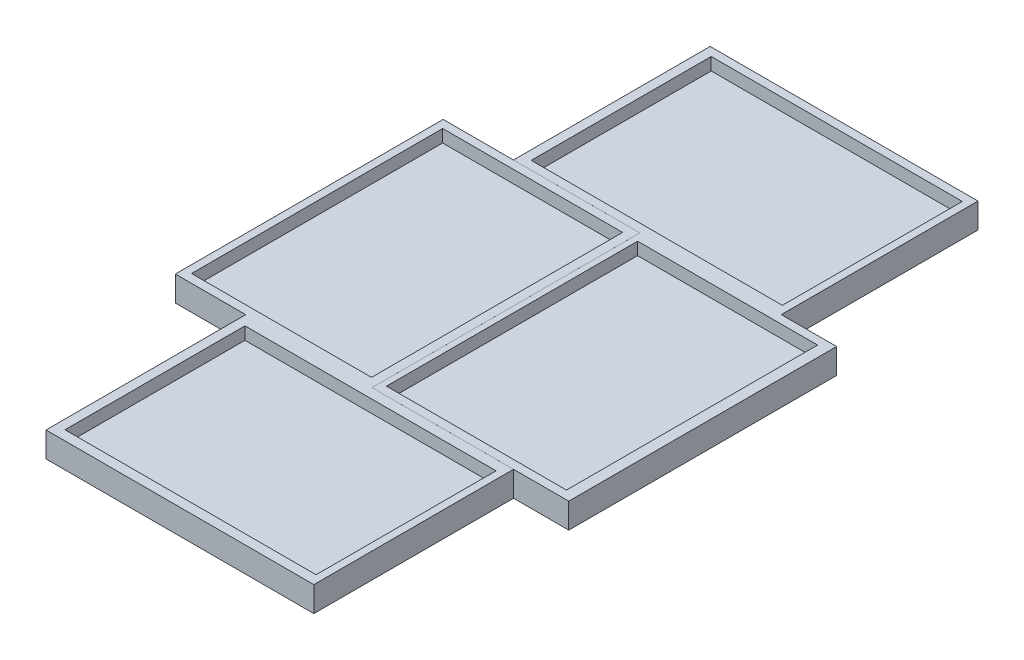
SolidWorks part; units mm, degrees
ref_plane "前视基准面" through (0, 0, 0) normal (0, 0, 1) x (1, 0, 0)
ref_plane "上视基准面" through (0, 0, 0) normal (0, 1, 0) x (1, 0, 0)
ref_plane "右视基准面" through (0, 0, 0) normal (1, 0, 0) x (0, 0, -1)
sketch "草图1" plane through (0, 0, 0) normal (0, 1, 0) x (1, 0, 0)
  line L1 (-27.6899, 58.9972) -> (36.3101, 58.9972)
  line L2 (-27.6899, 58.9972) -> (-27.6899, 11.9972)
  line L3 (-27.6899, 11.9972) -> (36.3101, 11.9972)
  line L4 (36.3101, 58.9972) -> (36.3101, 11.9972)
  line L8 (-27.6665, -52.0046) -> (36.3335, -52.0046)
  line L9 (-27.6665, -52.0046) -> (-27.6665, -99.7238)
  line L10 (-27.6665, -99.7238) -> (36.3335, -99.7238)
  line L11 (36.3335, -52.0046) -> (36.3335, -99.7238)
  line L12 (2.5191, 11.9972) -> (49.5191, 11.9972)
  line L13 (-44.4826, 11.9954) -> (2.5174, 11.9954)
  line L14 (-44.4826, 11.9954) -> (-44.4826, -52.0046)
  line L15 (-44.4826, -52.0046) -> (2.5174, -52.0046)
  line L16 (2.5174, 11.9954) -> (2.5174, -52.0046)
  line L17 (2.5191, 11.9972) -> (2.5191, -52.0028)
  line L18 (2.5191, -52.0028) -> (49.5191, -52.0028)
  line L19 (49.5191, 11.9972) -> (49.5191, -52.0028)
  dimension "D1" = 64
  dimension "D2" = 47
  dimension "D3" = 64
  dimension "D4" = 47
extrude "凸台-拉伸1" add sketch "草图1" along normal blind 6 contours L4 L1 L2 L3 | L19 L12 L3 L17 L18 | L11 L8 L9 L10 | L14 L13 L16 L15
sketch "草图2" plane through (0, 6, 0) normal (0, 1, 0) x (1, 0, 0)
  line L0 (-25.481, 57.0389) -> (34.519, 57.0389)
  line L1 (-25.4416, -54.4076) -> (34.5584, -54.4076)
  line L2 (-25.4416, -54.4076) -> (-25.4416, -97.4076)
  line L3 (-25.4416, -97.4076) -> (34.5584, -97.4076)
  line L4 (34.5584, -54.4076) -> (34.5584, -97.4076)
  line L5 (-25.481, 57.0389) -> (-25.481, 14.0389)
  line L6 (-25.481, 14.0389) -> (34.519, 14.0389)
  line L7 (34.519, 57.0389) -> (34.519, 14.0389)
  line L8 (3.9484, 10.0228) -> (46.9484, 10.0228)
  line L9 (-42.6608, 10.0477) -> (0.3392, 10.0477)
  line L10 (-42.6608, 10.0477) -> (-42.6608, -49.9523)
  line L11 (-42.6608, -49.9523) -> (0.3392, -49.9523)
  line L12 (0.3392, 10.0477) -> (0.3392, -49.9523)
  line L13 (3.9484, 10.0228) -> (3.9484, -49.9772)
  line L14 (3.9484, -49.9772) -> (46.9484, -49.9772)
  line L15 (46.9484, 10.0228) -> (46.9484, -49.9772)
  dimension "D1" = 43
  dimension "D2" = 60
  dimension "D3" = 60
  dimension "D4" = 43
extrude "切除-拉伸1" cut sketch "草图2" against normal blind 3
